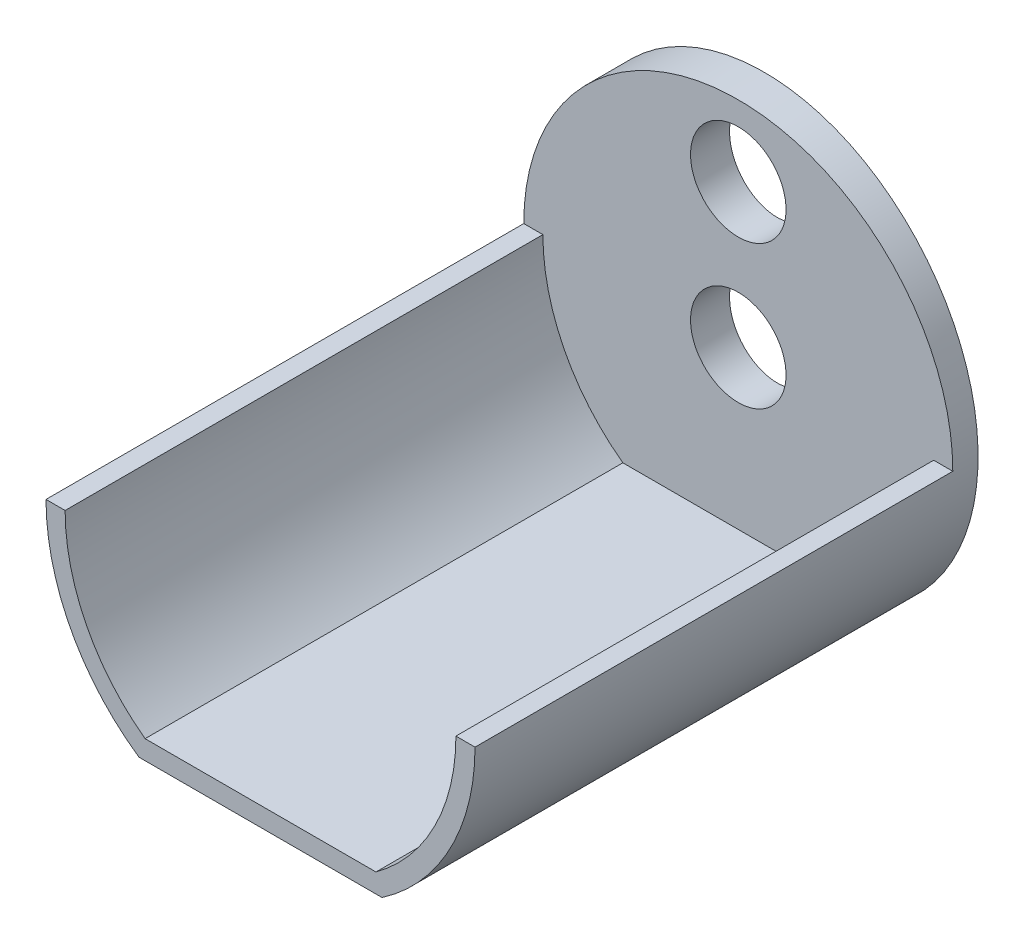
SolidWorks part; units mm, degrees
ref_plane "Front Plane" through (0, 0, 0) normal (0, 0, 1) x (1, 0, 0)
ref_plane "Top Plane" through (0, 0, 0) normal (0, 1, 0) x (1, 0, 0)
ref_plane "Right Plane" through (0, 0, 0) normal (1, 0, 0) x (0, 0, -1)
sketch "Sketch1" plane through (0, 0, 0) normal (0, 0, 1) x (1, 0, 0)
  circle A0 centre (0, 0) radius 22.45
  dimension "D1" = 44.9
extrude "Boss-Extrude1" add sketch "Sketch1" along normal blind 5
sketch "Sketch2" plane through (0, 0, 0) normal (0, 0, -1) x (-1, 0, 0)
  line L0 (0, 0) -> (0, 15) construction
  circle A0 centre (0, 0) radius 5
  circle A1 centre (0, 15) radius 5
  dimension "D1" = 10
  dimension "D2" = 15
  dimension "D3" = 10
extrude "Cut-Extrude1" cut sketch "Sketch2" against normal blind 5
sketch "Sketch3" plane through (0, 0, 5) normal (0, 0, 1) x (1, 0, 0)
  line L1 (-12.7182, -18.5) -> (12.7182, -18.5)
  line L3 (-15.2234, -16.5) -> (15.2234, -16.5)
  line L5 (-15.2234, -16.5) -> (15.2234, -16.5) construction
  line L6 (-15.2234, -16.5) -> (15.2234, -16.5) construction
  circle A0 centre (0, 0) radius 22.45 construction
  arc A1 (-15.2234, -16.5) -> (-12.7182, -18.5) centre (0, 0) ccw
  arc A2 (12.7182, -18.5) -> (15.2234, -16.5) centre (0, 0) ccw
  point P0 (0, -16.5)
  point P2 (0, 0)
  point P5 (-0.4011, -16.4951)
  point P7 (-0.9873, -16.4704)
  point P11 (0, 0)
  point P12 (-15, -16.5)
  point P15 (-15.1972, -16.5242)
  point P16 (15.2025, -16.5)
  point P17 (15.0993, -16.6136)
  dimension "D1" = 16.5
  dimension "D3" = 2
extrude "Boss-Extrude2" add sketch "Sketch3" along normal blind 50 contours A1 L1 A2 L3
sketch "Sketch5" plane through (0, 0, 5) normal (0, 0, 1) x (1, 0, 0)
  line L0 (-15.2234, -16.5) -> (-12.0811, -16.5)
  line L1 (-20.45, 0) -> (-22.45, 0)
  line L3 (20.45, 0) -> (22.45, 0)
  line L4 (-15.2234, -16.5) -> (15.2234, -16.5) construction
  line L6 (15.2234, -16.5) -> (12.0811, -16.5)
  line L7 (-15.2234, -16.5) -> (15.2234, -16.5) construction
  arc A3 (15.2234, -16.5) -> (22.45, 0) centre (0, 0) ccw
  arc A4 (-22.45, 0) -> (-15.2234, -16.5) centre (0, 0) ccw
  arc A5 (15.2234, -16.5) -> (-15.2234, -16.5) centre (0, 0) ccw construction
  arc A6 (-20.45, 0) -> (-13.8672, -15.0301) centre (0, 0) ccw
  arc A8 (11.5852, -16.8519) -> (13.8672, -15.0301) centre (0, 0) ccw
  arc A9 (13.8672, -15.0301) -> (-13.8672, -15.0301) centre (0, 0) ccw
  arc A10 (-13.8672, -15.0301) -> (-11.5852, -16.8519) centre (0, 0) ccw
  arc A11 (12.0811, -16.5) -> (13.8672, -15.0301) centre (0, 0) ccw
  arc A12 (13.8672, -15.0301) -> (20.45, 0) centre (0, 0) ccw
  arc A13 (-13.8672, -15.0301) -> (-12.0811, -16.5) centre (0, 0) ccw
  point P2 (0, 0)
  dimension "D1" = 2
extrude "Boss-Extrude5" add sketch "Sketch5" along normal blind 50
sketch "Sketch6" plane through (0, 0, 0) normal (0, 1, 0) x (1, 0, 0)
  line L0 (-22.45, 0) -> (22.45, 0)
  line L1 (22.45, 0) -> (22.45, -2.3531)
  line L2 (22.45, -5) -> (22.45, 0) construction
  line L3 (22.45, -2.3531) -> (-22.45, 0)
  point P4 (0, 0)
  dimension "D1" = 3
extrude "Cut-Extrude3" cut sketch "Sketch6" against normal through all both and the other way through all
